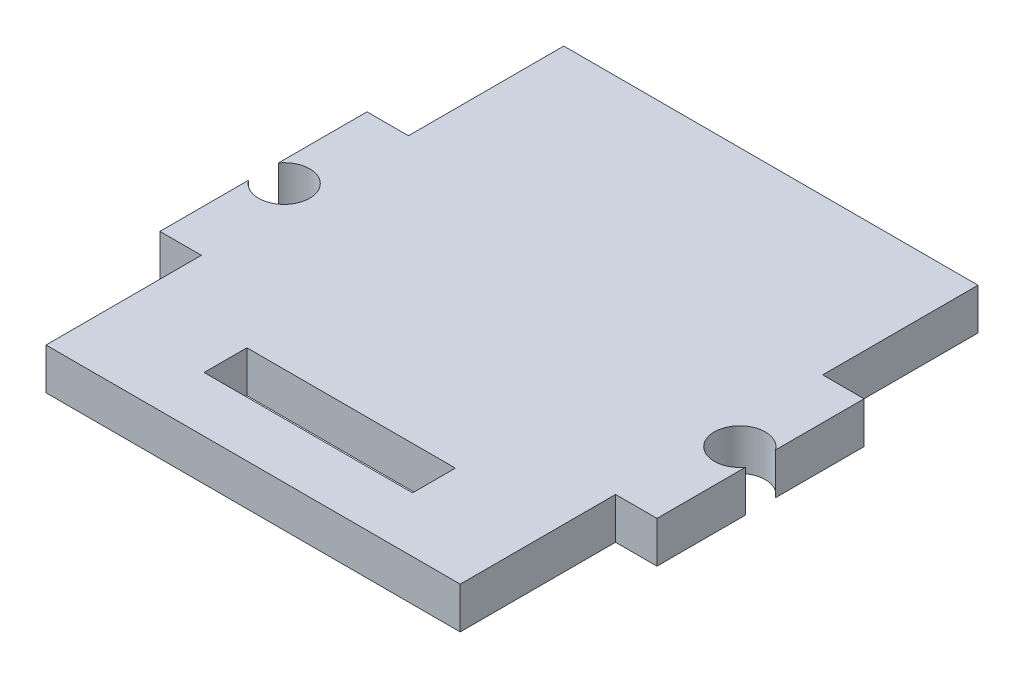
SolidWorks part; units mm, degrees
ref_plane "Front" through (0, 0, 0) normal (0, 0, 1) x (1, 0, 0)
ref_plane "Top" through (0, 0, 0) normal (0, 1, 0) x (1, 0, 0)
ref_plane "Right" through (0, 0, 0) normal (1, 0, 0) x (0, 0, -1)
sketch "Sketch1" plane through (0, 0, 0) normal (0, 1, 0) x (1, 0, 0)
  line L1 (-15, 18.75) -> (15, 18.75)
  line L2 (-15, 18.75) -> (-15, -18.75)
  line L3 (-15, -18.75) -> (15, -18.75)
  line L4 (15, 18.75) -> (15, -18.75)
  line L5 (-15, 18.75) -> (15, -18.75) construction
  line L6 (-15, -18.75) -> (15, 18.75) construction
  point P0 (0, 0)
  dimension "D1" = 30
  dimension "D2" = 37.5
extrude "Boss-Extrude1" add sketch "Sketch1" along normal blind 3
sketch "Sketch2" plane through (0, 3, 0) normal (0, 1, 0) x (1, 0, 0)
  line L0 (-15, 18.75) -> (-15, -18.75) construction
  line L1 (-15, -7.5) -> (-18, -7.5)
  line L2 (-15, -7.5) -> (-15, 7.5)
  line L3 (-15, 7.5) -> (-18, 7.5)
  line L4 (-18, -7.5) -> (-18, 7.5)
  line L5 (15, -18.75) -> (15, 18.75) construction
  line L6 (15, -7.5) -> (18, -7.5)
  line L7 (15, -7.5) -> (15, 7.5)
  line L8 (15, 7.5) -> (18, 7.5)
  line L9 (18, -7.5) -> (18, 7.5)
  line L10 (15, 0) -> (0, 0) construction
  line L11 (0, 0) -> (-15, 0) construction
  dimension "D1" = 15
  dimension "D2" = 3
extrude "Boss-Extrude2" add sketch "Sketch2" against normal blind 3
sketch "Sketch3" plane through (0, 3, 0) normal (0, 1, 0) x (1, 0, 0)
  line L0 (-16.5, 0) -> (0, 0) construction
  line L1 (0, 0) -> (16.5, 0) construction
  line L2 (-18, 7.5) -> (-18, -7.5) construction
  circle A0 centre (-16.5, 0) radius 1.85
  circle A1 centre (16.5, 0) radius 1.85
  dimension "D1" = 3.7
  dimension "D2" = 1.5
extrude "Cut-Extrude1" cut sketch "Sketch3" against normal through all
sketch "Sketch4" plane through (0, 3, 0) normal (0, 1, 0) x (1, 0, 0)
  line L0 (-15, -18.75) -> (15, -18.75) construction
  line L1 (-7.55, -14.75) -> (7.55, -14.75)
  line L2 (-7.55, -14.75) -> (-7.55, -11.65)
  line L3 (-7.55, -11.65) -> (7.55, -11.65)
  line L4 (7.55, -14.75) -> (7.55, -11.65)
  line L6 (0, -11.65) -> (0, 0) construction
  dimension "D1" = 3.1
  dimension "D2" = 15.1
  dimension "D3" = 4
extrude "Cut-Extrude2" cut sketch "Sketch4" against normal through all
